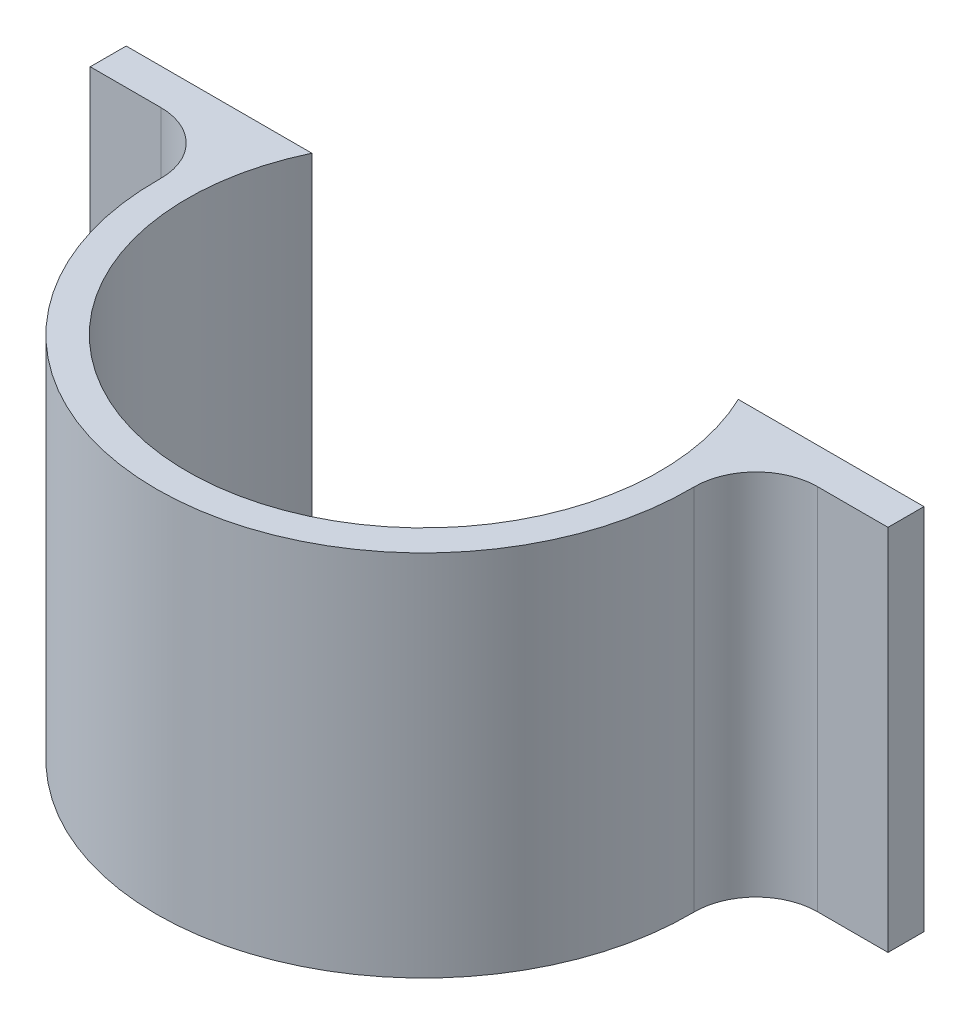
SolidWorks part; units mm, degrees
ref_plane "Front Plane" through (0, 0, 0) normal (0, 0, 1) x (1, 0, 0)
ref_plane "Top Plane" through (0, 0, 0) normal (0, 1, 0) x (1, 0, 0)
ref_plane "Right Plane" through (0, 0, 0) normal (1, 0, 0) x (0, 0, -1)
sketch "Sketch1" plane through (0, 0, 0) normal (0, 1, 0) x (1, 0, 0)
  line L0 (34.7526, 16.5683) -> (65, 16.5683)
  line L7 (0, 16.5683) -> (0, 0)
  line L8 (-65, 16.5683) -> (-34.7526, 16.5683)
  line L9 (-65, 16.5683) -> (-65, 10.7116)
  line L16 (-65, 10.7116) -> (-42.1606, 10.7116)
  line L17 (65, 16.5683) -> (65, 10.7116)
  line L20 (0, 16.5683) -> (0, 13.6399) construction
  line L22 (42.1606, 10.7116) -> (65, 10.7116)
  arc A0 (-34.7526, 16.5683) -> (34.7526, 16.5683) centre (0, 0) ccw
  arc A2 (-42.1606, 10.7116) -> (42.1606, 10.7116) centre (0, 0) ccw
  point P5 (0, 21.75)
  point P8 (0, 21.75)
  dimension "D1" = 77
  dimension "D3" = 130
extrude "Boss-Extrude2" add sketch "Sketch1" along normal blind 60 contours L16 A2 L22 L17 L0 A0 L8 L9
fillet "Fillet3" radius 10 2 edges at (-42.1606, 30, -10.7116) (42.1606, 30, -10.7116)
